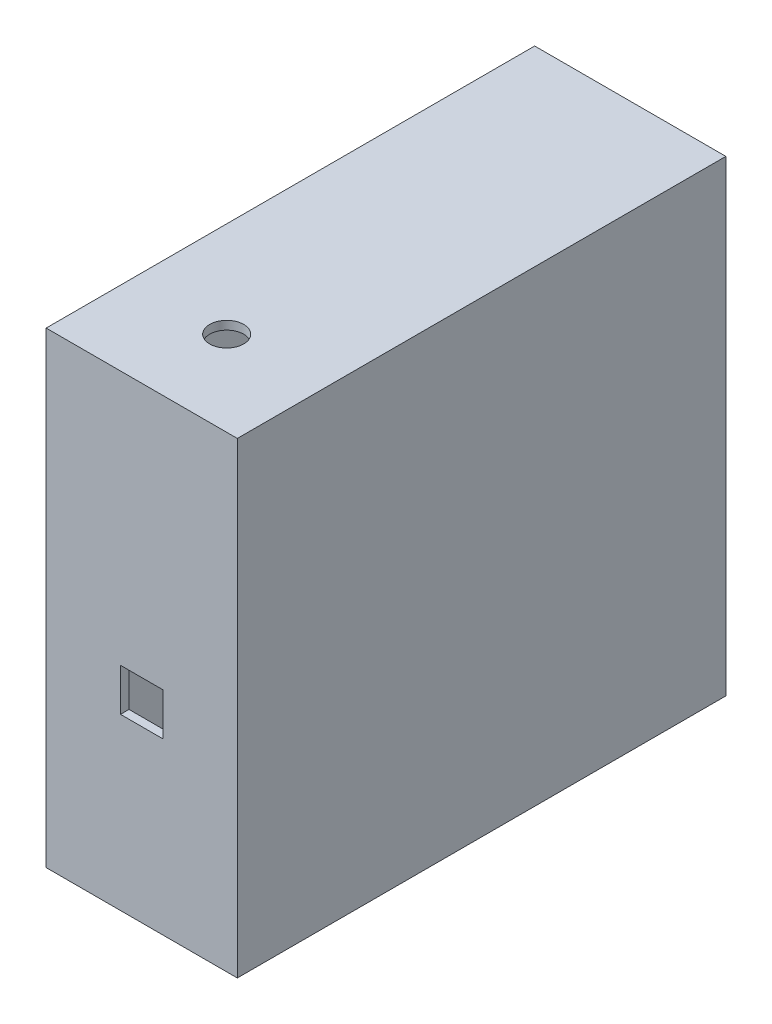
SolidWorks part; units mm, degrees
ref_plane "Front Plane" through (0, 0, 0) normal (1, 0, 0) x (0, 1, 0)
ref_plane "Top Plane" through (0, 0, 0) normal (0, 0, 1) x (0, 1, 0)
ref_plane "Right Plane" through (0, 0, 0) normal (0, 1, 0) x (-1, 0, 0)
sketch "Sketch1" plane through (0, 0, 0) normal (0, 0, 1) x (0, 1, 0)
  line L1 (0, 0) -> (110, 0)
  line L2 (0, 0) -> (0, 45)
  line L3 (0, 45) -> (110, 45)
  line L4 (110, 0) -> (110, 45)
  dimension "D1" = 110
  dimension "D2" = 45
extrude "Boss-Extrude1" add sketch "Sketch1" along normal blind 115
shell "Shell1" thickness 2
sketch "Sketch2" plane through (0, 0, 0) normal (0, -1, 0) x (1, 0, 0)
  line L1 (-45, 25) -> (-22.5, 25) construction
  line L2 (-45, 115) -> (-45, 0) construction
  line L3 (-22.5, 25) -> (0, 25) construction
  line L4 (0, 115) -> (0, 0) construction
  line L5 (-45, 0) -> (0, 0) construction
  circle A0 centre (-22.5, 25) radius 16.5
  dimension "D1" = 33
  dimension "D2" = 25
extrude "Cut-Extrude1" cut sketch "Sketch2" against normal up to next
sketch "Sketch3" plane through (0, 0, 115) normal (0, 0, 1) x (1, 0, 0)
  line L0 (-22.5, 0) -> (-22.5, 40) construction
  line L1 (-27.5, 50) -> (-17.5, 50)
  line L2 (-27.5, 50) -> (-27.5, 40)
  line L3 (-27.5, 40) -> (-17.5, 40)
  line L4 (-17.5, 50) -> (-17.5, 40)
  line L5 (-45, 0) -> (0, 0) construction
  dimension "D1" = 10
  dimension "D2" = 10
  dimension "D3" = 40
extrude "Cut-Extrude2" cut sketch "Sketch3" against normal up to next
sketch "Sketch4" plane through (0, 110, 0) normal (0, 1, 0) x (-1, 0, 0)
  line L0 (0, 95) -> (22.5, 95) construction
  line L1 (0, 115) -> (0, 0) construction
  line L2 (22.5, 95) -> (45, 95) construction
  line L3 (45, 115) -> (45, 0) construction
  line L4 (0, 115) -> (45, 115) construction
  circle A0 centre (22.5, 95) radius 4
  point P8 (0, 0)
  dimension "D1" = 8
  dimension "D2" = 20
extrude "Cut-Extrude3" cut sketch "Sketch4" against normal up to next
